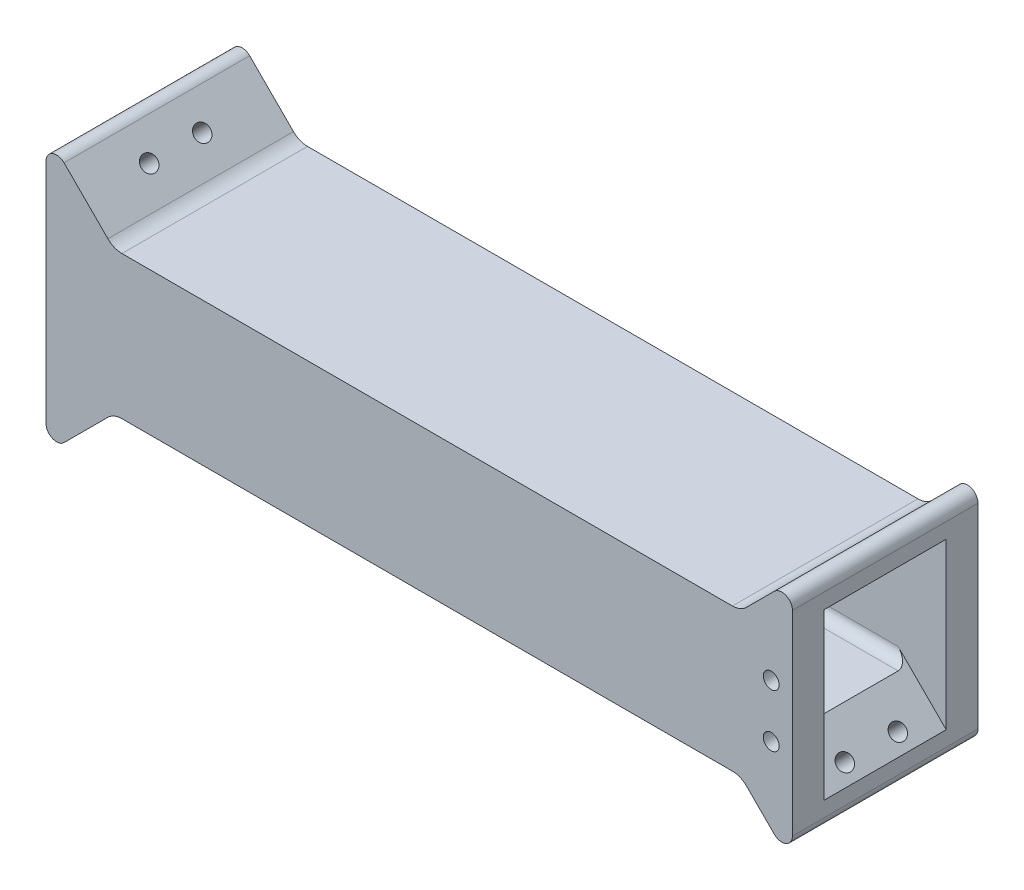
SolidWorks part; units mm, degrees
ref_plane "前视基准面" through (0, 0, 0) normal (0, 0, 1) x (1, 0, 0)
ref_plane "上视基准面" through (0, 0, 0) normal (0, 1, 0) x (1, 0, 0)
ref_plane "右视基准面" through (0, 0, 0) normal (1, 0, 0) x (0, 0, -1)
other "Configuration Table"
sketch "草图1" plane through (0, 0, 0) normal (0, 0, 1) x (1, 0, 0)
  line L0 (158.0713, -50) -> (42.9242, -50) construction
  line L1 (42.9242, -50) -> (42.9242, -53) construction
  line L2 (42.9242, -53) -> (158.0713, -53) construction
  line L3 (167.282, -61.9056) -> (169.4034, -59.7843) construction
  line L4 (169.4034, -59.7843) -> (160.7135, -51.0944) construction
  line L5 (158.5922, -53.2157) -> (167.282, -61.9056) construction
  line L6 (169.4034, -13.2157) -> (167.282, -11.0944) construction
  line L7 (167.282, -11.0944) -> (158.5922, -19.7843) construction
  line L8 (160.7135, -21.9056) -> (169.4034, -13.2157) construction
  line L9 (158.0713, -20) -> (42.9242, -20) construction
  line L10 (42.9242, -20) -> (42.9242, -23) construction
  line L11 (42.9242, -23) -> (158.0713, -23) construction
  line L12 (169.4034, -13.2157) -> (160.7135, -21.9056) construction
  line L13 (158.0713, -50) -> (42.9242, -50)
  line L14 (42.9242, -50) -> (42.9242, -53)
  line L15 (42.9242, -53) -> (158.0713, -53)
  line L16 (167.282, -61.9056) -> (169.4034, -59.7843)
  line L17 (169.4034, -59.7843) -> (160.7135, -51.0944)
  line L18 (158.5922, -53.2157) -> (167.282, -61.9056)
  line L19 (169.4034, -13.2157) -> (167.282, -11.0944)
  line L20 (167.282, -11.0944) -> (158.5922, -19.7843)
  line L21 (160.7135, -21.9056) -> (169.4034, -13.2157)
  line L22 (158.0713, -20) -> (42.9242, -20)
  line L23 (42.9242, -20) -> (42.9242, -23)
  line L24 (42.9242, -23) -> (158.0713, -23)
  line L25 (169.4034, -13.2157) -> (160.7135, -21.9056)
  line L26 (30.7135, -64.9056) -> (42.4034, -53.2157) construction
  line L27 (40.282, -51.0944) -> (28.5922, -62.7843) construction
  line L28 (28.5922, -62.7843) -> (30.7135, -64.9056) construction
  line L29 (42.9242, -53) -> (42.9242, -50) construction
  line L30 (42.9242, -23) -> (42.9242, -20) construction
  line L32 (42.4034, -19.7843) -> (30.7135, -8.0944) construction
  line L33 (30.7135, -8.0944) -> (28.5922, -10.2157) construction
  line L34 (30.7135, -64.9056) -> (42.4034, -53.2157)
  line L35 (40.282, -51.0944) -> (28.5922, -62.7843)
  line L36 (28.5922, -62.7843) -> (30.7135, -64.9056)
  line L37 (42.9242, -53) -> (42.9242, -50)
  line L38 (42.9242, -23) -> (42.9242, -20)
  line L39 (28.5922, -10.2157) -> (40.282, -21.9056)
  line L40 (42.4034, -19.7843) -> (30.7135, -8.0944)
  line L41 (30.7135, -8.0944) -> (28.5922, -10.2157)
  line L42 (169.4034, -13.2157) -> (169.4034, -59.7843)
  line L43 (28.5922, -10.2157) -> (28.5922, -62.7843)
  arc A0 (158.5922, -53.2157) -> (158.0713, -53) centre (158.0713, -53.7366) ccw construction
  arc A1 (160.7135, -51.0944) -> (158.0713, -50) centre (158.0713, -53.7366) ccw construction
  arc A2 (158.0713, -23) -> (160.7135, -21.9056) centre (158.0713, -19.2634) ccw construction
  arc A3 (158.0713, -20) -> (158.5922, -19.7843) centre (158.0713, -19.2634) ccw construction
  arc A4 (158.5922, -53.2157) -> (158.0713, -53) centre (158.0713, -53.7366) ccw
  arc A5 (160.7135, -51.0944) -> (158.0713, -50) centre (158.0713, -53.7366) ccw
  arc A6 (158.0713, -23) -> (160.7135, -21.9056) centre (158.0713, -19.2634) ccw
  arc A7 (158.0713, -20) -> (158.5922, -19.7843) centre (158.0713, -19.2634) ccw
  arc A8 (42.9242, -53) -> (42.4034, -53.2157) centre (42.9242, -53.7366) ccw construction
  arc A9 (42.9242, -50) -> (40.282, -51.0944) centre (42.9242, -53.7366) ccw construction
  arc A10 (40.282, -21.9056) -> (42.9242, -23) centre (42.9242, -19.2634) ccw construction
  arc A11 (42.4034, -19.7843) -> (42.9242, -20) centre (42.9242, -19.2634) ccw construction
  arc A12 (42.9242, -53) -> (42.4034, -53.2157) centre (42.9242, -53.7366) ccw
  arc A13 (42.9242, -50) -> (40.282, -51.0944) centre (42.9242, -53.7366) ccw
  arc A14 (40.282, -21.9056) -> (42.9242, -23) centre (42.9242, -19.2634) ccw
  arc A15 (42.4034, -19.7843) -> (42.9242, -20) centre (42.9242, -19.2634) ccw
extrude "凸台-拉伸1" add sketch "草图1" against normal blind 35 contours A14 L39 L43 L35 A13 L13 A5 L17 L42 L21 A6 L24
sketch "草图2" plane through (0, 0, 0) normal (0, 0, 1) x (1, 0, 0)
  line L0 (28.6022, -10.2399) -> (28.6022, -62.7601)
  line L1 (28.6022, -62.7601) -> (40.275, -51.0874)
  line L2 (42.9242, -49.99) -> (158.0713, -49.99)
  line L3 (160.7206, -51.0874) -> (169.3934, -59.7601)
  line L4 (169.3934, -59.7601) -> (169.3934, -13.2399)
  line L5 (169.3934, -13.2399) -> (160.7206, -21.9126)
  line L6 (158.0713, -23.01) -> (42.9242, -23.01)
  line L7 (40.275, -21.9126) -> (28.6022, -10.2399)
  line L8 (40.282, -21.9056) -> (28.5922, -10.2157)
  line L9 (28.5922, -10.2157) -> (28.5922, -62.7843)
  line L10 (28.5922, -62.7843) -> (40.282, -51.0944)
  line L11 (42.9242, -50) -> (158.0713, -50)
  line L12 (160.7135, -51.0944) -> (169.4034, -59.7843)
  line L13 (169.4034, -59.7843) -> (169.4034, -13.2157)
  line L14 (169.4034, -13.2157) -> (160.7135, -21.9056)
  line L15 (158.0713, -23) -> (42.9242, -23)
  line L16 (40.282, -21.9056) -> (28.5922, -10.2157)
  line L17 (28.5922, -10.2157) -> (28.5922, -62.7843)
  line L18 (28.5922, -62.7843) -> (40.282, -51.0944)
  line L19 (42.9242, -50) -> (158.0713, -50)
  line L20 (160.7135, -51.0944) -> (169.4034, -59.7843)
  line L21 (169.4034, -59.7843) -> (169.4034, -13.2157)
  line L22 (169.4034, -13.2157) -> (160.7135, -21.9056)
  line L23 (158.0713, -23) -> (42.9242, -23)
  arc A0 (42.9242, -49.99) -> (40.275, -51.0874) centre (42.9242, -53.7366) ccw
  arc A1 (160.7206, -51.0874) -> (158.0713, -49.99) centre (158.0713, -53.7366) ccw
  arc A2 (158.0713, -23.01) -> (160.7206, -21.9126) centre (158.0713, -19.2634) ccw
  arc A3 (40.275, -21.9126) -> (42.9242, -23.01) centre (42.9242, -19.2634) ccw
  arc A4 (40.282, -21.9056) -> (42.9242, -23) centre (42.9242, -19.2634) ccw
  arc A5 (42.9242, -50) -> (40.282, -51.0944) centre (42.9242, -53.7366) ccw
  arc A6 (160.7135, -51.0944) -> (158.0713, -50) centre (158.0713, -53.7366) ccw
  arc A7 (158.0713, -23) -> (160.7135, -21.9056) centre (158.0713, -19.2634) ccw
  arc A8 (40.282, -21.9056) -> (42.9242, -23) centre (42.9242, -19.2634) ccw
  arc A9 (42.9242, -50) -> (40.282, -51.0944) centre (42.9242, -53.7366) ccw
  arc A10 (160.7135, -51.0944) -> (158.0713, -50) centre (158.0713, -53.7366) ccw
  arc A11 (158.0713, -23) -> (160.7135, -21.9056) centre (158.0713, -19.2634) ccw
  dimension "D1" = 0
  dimension "D2" = 0.01
extrude "切除-拉伸1" cut sketch "草图2" against normal through all
sketch "草图3" plane through (169.3934, 0, 0) normal (1, 0, 0) x (0, 0, -1)
  line L0 (0, -13.2399) -> (35, -59.7601) construction
  line L1 (6, -28.01) -> (29, -28.01)
  line L2 (6, -28.01) -> (6, -44.99)
  line L3 (6, -44.99) -> (29, -44.99)
  line L4 (29, -28.01) -> (29, -44.99)
  line L5 (6, -28.01) -> (29, -44.99) construction
  line L6 (6, -44.99) -> (29, -28.01) construction
  line L7 (0, -59.7601) -> (35, -13.2399) construction
  line L8 (35, -59.7601) -> (35, -13.2399) construction
  line L9 (0, -59.7601) -> (0, -13.2399) construction
  line L10 (35, -23.01) -> (0, -23.01) construction
  line L11 (35, -23.01) -> (0, -23.01)
  point P0 (17.5, -36.5)
  point P14 (35, -13.4572)
  point P15 (17.5, -36.5)
  dimension "D1" = 6
  dimension "D2" = 5
extrude "切除-拉伸2" cut sketch "草图3" against normal through all contours L4 L1 L2 L3
ref_plane "基准面1" through (36.7961, -36.7961, 0) normal (0.7071, -0.7071, 0) x (0, 0, -1)
sketch "草图5" plane through (36.7961, -36.7961, 0) normal (0.7071, -0.7071, 0) x (0, 0, -1)
  line L0 (6, -11.5879) -> (29, -11.5879) construction
  line L1 (6, -11.5879) -> (29, -11.5879)
  line L2 (6, -4.0879) -> (29, -4.0879)
  line L3 (6, -4.0879) -> (6, -19.0879)
  line L4 (29, -4.0879) -> (29, -19.0879)
  line L5 (6, -19.0879) -> (29, -19.0879)
  line L6 (6, -4.0879) -> (29, -19.0879) construction
  line L7 (29, -4.0879) -> (6, -19.0879) construction
  point P2 (17.592, -11.5879)
  point P3 (17.5, -11.5879)
  dimension "D1" = 15
extrude "切除-拉伸3" cut sketch "草图5" along normal blind 5 contours L3 L5 L4 L1 | L4 L2 L3 L1
sketch "草图6" plane through (40.3316, -40.3316, 0) normal (-0.7071, 0.7071, 0) x (0, 0, 1)
  line L0 (-29, -16.5879) -> (-6, -16.5879) construction
  line L1 (-6, -6.5879) -> (-6, -16.5879) construction
  circle A0 centre (-12, -13.5879) radius 1.5
  circle A1 centre (-22, -13.5879) radius 1.5
  dimension "D2" = 3
  dimension "D1" = 3
  dimension "D3" = 6
  dimension "D5" = 10
  dimension "D4" = 2
extrude "切除-拉伸4" cut sketch "草图6" against normal through all
ref_plane "基准面2" through (0, -36.5, 0) normal (0, 1, 0) x (1, 0, 0)
mirror "镜向1" about plane through (0, -36.5, 0) normal (0, 1, 0) of "切除-拉伸4", "切除-拉伸3"
ref_plane "基准面3" through (98.9978, 0, 0) normal (1, 0, 0) x (0, 0, -1)
mirror "镜向2" about plane through (98.9978, 0, 0) normal (1, 0, 0) of "镜向1", "切除-拉伸4", "切除-拉伸3"
fillet "圆角3" radius 2 8 edges at (98.9978, -44.99, -6) (98.9978, -28.01, -6) (98.9978, -28.01, -29) (98.9978, -44.99, -29) (28.6022, -10.2399, -17.5) (169.3934, -59.7601, -17.5) (169.3934, -13.2399, -17.5) (28.6022, -62.7601, -17.5)
sketch "草图7" plane through (0, 0, 0) normal (0, 0, 1) x (1, 0, 0)
  line L4 (169.3934, -36.5) -> (165.3934, -36.5) construction
  line L5 (169.3934, -54.9317) -> (169.3934, -18.0683) construction
  line L6 (165.3934, -31.5) -> (165.3934, -41.5) construction
  circle A2 centre (165.3934, -41.5) radius 1.5
  circle A3 centre (165.3934, -31.5) radius 1.5
  point P16 (165.3934, -36.5)
  dimension "D4" = 3
  dimension "D5" = 4
  dimension "D6" = 10
extrude "切除-拉伸5" cut sketch "草图7" against normal blind 8
